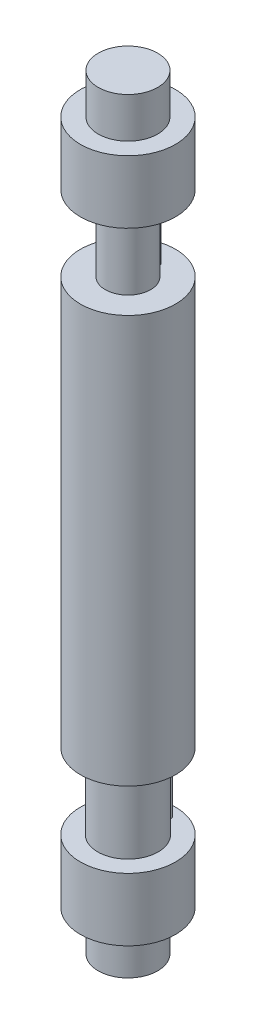
SolidWorks part; units mm, degrees
ref_plane "Front Plane" through (0, 0, 0) normal (0, 0, 1) x (1, 0, 0)
ref_plane "Top Plane" through (0, 0, 0) normal (0, 1, 0) x (1, 0, 0)
ref_plane "Right Plane" through (0, 0, 0) normal (1, 0, 0) x (0, 0, -1)
sketch "Sketch1" plane through (0, 0, 0) normal (0, 1, 0) x (1, 0, 0)
  circle A0 centre (0, 0) radius 12.5
  dimension "D1" = 25
extrude "Boss-Extrude1" add sketch "Sketch1" along normal blind 17
sketch "Sketch2" plane through (0, 17, 0) normal (0, 1, 0) x (1, 0, 0)
  circle A0 centre (0, 0) radius 20
  dimension "D1" = 40
extrude "Boss-Extrude2" add sketch "Sketch2" along normal blind 26.425
sketch "Sketch3" plane through (0, 43.425, 0) normal (0, 1, 0) x (1, 0, 0)
  circle A0 centre (0, 0) radius 12.7
  dimension "D1" = 25.4
extrude "Boss-Extrude3" add sketch "Sketch3" along normal blind 31.75
sketch "Sketch8" plane through (0, 75.175, 0) normal (0, 1, 0) x (1, 0, 0)
  line L0 (0, 0) -> (0, 33.8067) construction
  line L2 (3.175, 15.4717) -> (-3.175, 15.4717)
  line L3 (3.175, 15.4717) -> (3.175, 12.2967)
  line L4 (3.175, 12.2967) -> (-3.175, 12.2967)
  line L5 (-3.175, 15.4717) -> (-3.175, 12.2967)
  line L6 (3.175, 15.4717) -> (-3.175, 12.2967) construction
  line L7 (3.175, 12.2967) -> (-3.175, 15.4717) construction
  circle A0 centre (0, 0) radius 12.7 construction
  point P3 (0, 13.8842)
  dimension "D1" = 6.35
  dimension "D2" = 3.175
extrude "Boss-Extrude8" add sketch "Sketch8" against normal up to surface (31.75 mm away) up to face at (0, 43.425, 12.7)
sketch "Sketch4" plane through (0, 75.175, 0) normal (0, 1, 0) x (1, 0, 0)
  circle A0 centre (0, 0) radius 20
  dimension "D1" = 40
extrude "Boss-Extrude4" add sketch "Sketch4" along normal blind 171.45
sketch "Sketch5" plane through (0, 246.625, 0) normal (0, 1, 0) x (1, 0, 0)
  circle A0 centre (0, 0) radius 9.525
  dimension "D1" = 19.05
extrude "Boss-Extrude5" add sketch "Sketch5" along normal blind 31.75
sketch "Sketch9" plane through (0, 278.375, 0) normal (0, 1, 0) x (1, 0, 0)
  line L0 (0, 0) -> (0, 32.7798) construction
  line L2 (2.3813, 11.6038) -> (-2.3812, 11.6038)
  line L3 (2.3813, 11.6038) -> (2.3813, 9.2225)
  line L4 (2.3813, 9.2225) -> (-2.3813, 9.2225)
  line L5 (-2.3812, 11.6038) -> (-2.3813, 9.2225)
  line L6 (2.3813, 11.6038) -> (-2.3813, 9.2225) construction
  line L7 (2.3813, 9.2225) -> (-2.3812, 11.6038) construction
  circle A0 centre (0, 0) radius 9.525 construction
  point P3 (0, 10.4132)
  dimension "D1" = 2.3813
  dimension "D2" = 4.7625
extrude "Boss-Extrude9" add sketch "Sketch9" against normal up to surface (31.75 mm away) up to face at (0, 246.625, 9.525)
sketch "Sketch6" plane through (0, 278.375, 0) normal (0, 1, 0) x (1, 0, 0)
  circle A0 centre (0, 0) radius 20
  dimension "D1" = 40
extrude "Boss-Extrude6" add sketch "Sketch6" along normal blind 26.425
sketch "Sketch7" plane through (0, 304.8, 0) normal (0, 1, 0) x (1, 0, 0)
  circle A0 centre (0, 0) radius 12.5
  dimension "D1" = 25
extrude "Boss-Extrude7" add sketch "Sketch7" along normal blind 17
